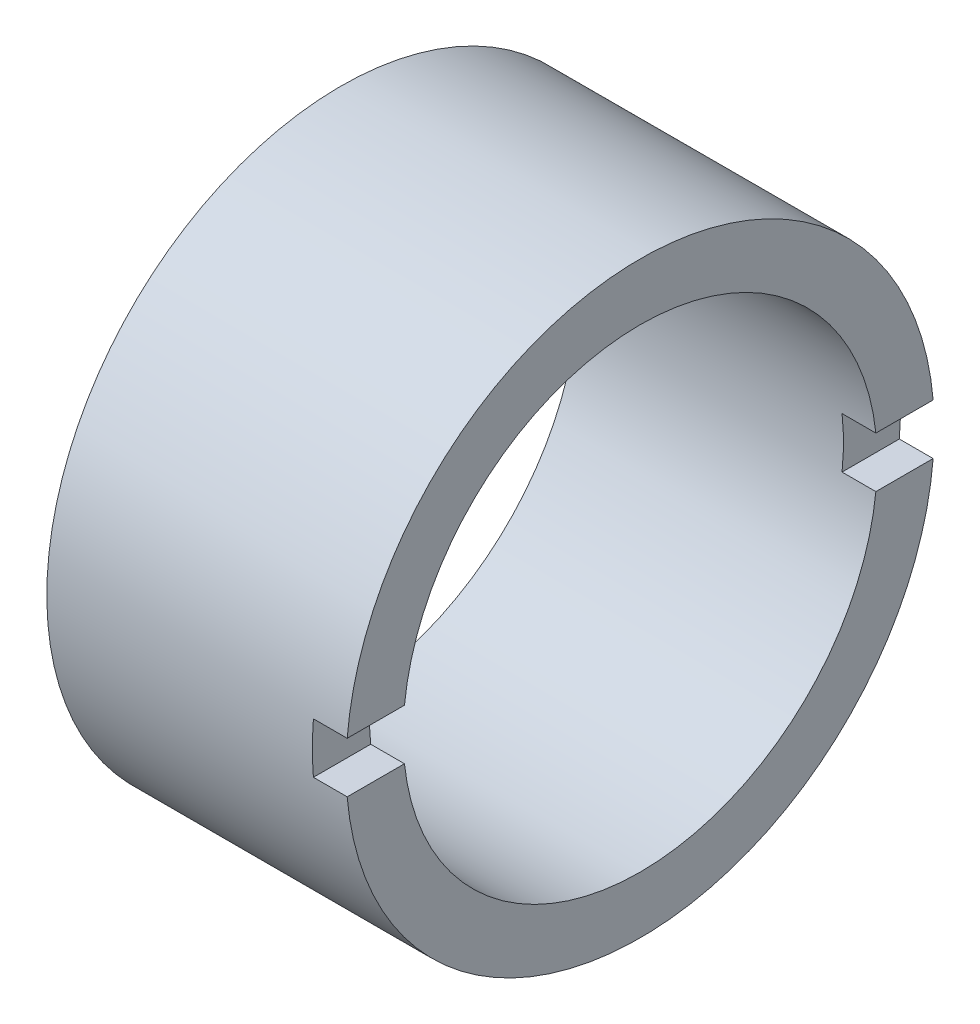
SolidWorks part; units mm, degrees
ref_plane "Front Plane" through (0, 0, 0) normal (0, 0, 1) x (1, 0, 0)
ref_plane "Top Plane" through (0, 0, 0) normal (0, 1, 0) x (1, 0, 0)
ref_plane "Right Plane" through (0, 0, 0) normal (1, 0, 0) x (0, 0, -1)
sketch "Sketch2" plane through (0, 0, 0) normal (1, 0, 0) x (0, 0, -1)
  circle A0 centre (0, 0) radius 26.5303
  circle A1 centre (0, 0) radius 21.3868
  dimension "D1" = 53.0606
  dimension "D2" = 42.7736
extrude "Boss-Extrude1" add sketch "Sketch2" along normal blind 27.0002
sketch "Sketch3" plane through (0, 0, 0) normal (0, 0, 1) x (1, 0, 0)
  line L0 (0, 0) -> (25.4762, 0) construction
  line L1 (27.0002, -2.286) -> (23.9522, -2.286)
  line L2 (27.0002, -2.286) -> (27.0002, 2.286)
  line L3 (27.0002, 2.286) -> (23.9522, 2.286)
  line L4 (23.9522, -2.286) -> (23.9522, 2.286)
  line L5 (27.0002, -2.286) -> (23.9522, 2.286) construction
  line L6 (27.0002, 2.286) -> (23.9522, -2.286) construction
  line L7 (0, 26.5303) -> (0, -26.5303) construction
  line L8 (27.0002, -26.5303) -> (27.0002, 26.5303) construction
  point P0 (25.4762, 0)
  dimension "D1" = 23.9522
  dimension "D2" = 4.572
extrude "Cut-Extrude1" cut sketch "Sketch3" against normal through all and the other way through all
ref_plane "Midmagnet plane" through (13.5001, 0, 0) normal (1, 0, 0) x (0, 0, -1)
